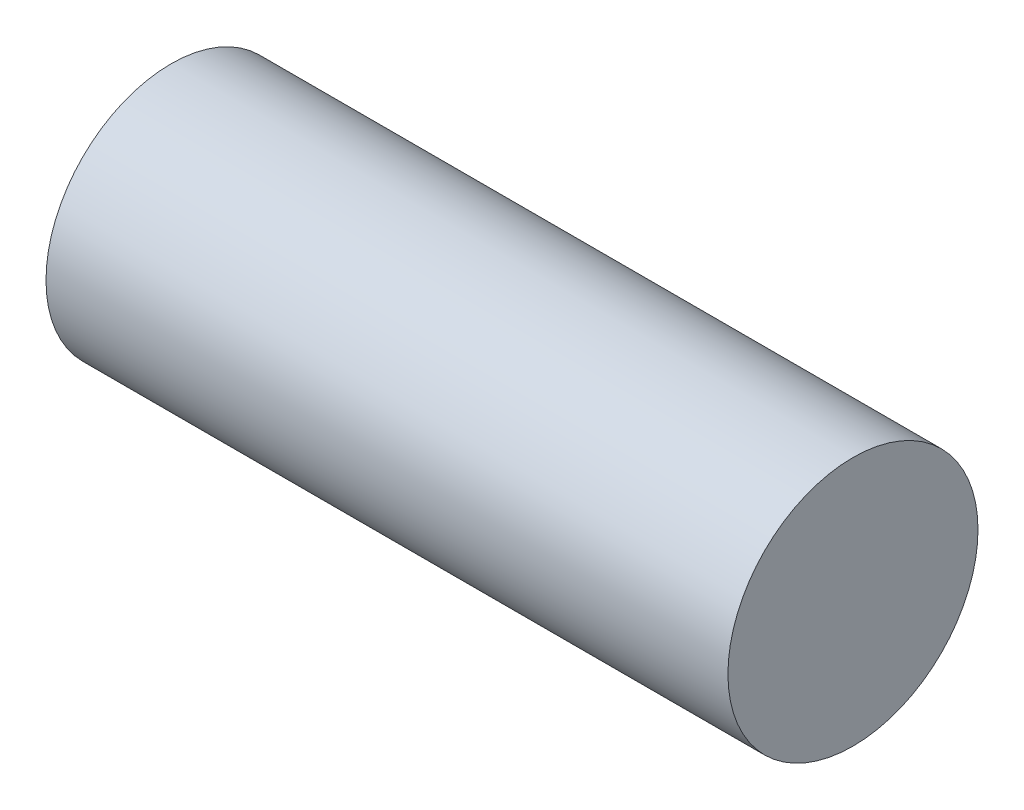
SolidWorks part; units mm, degrees
material "AISI 4340 Steel, normalized"
ref_plane "Front Plane" through (0, 0, 0) normal (0, 0, 1) x (1, 0, 0)
ref_plane "Top Plane" through (0, 0, 0) normal (0, 1, 0) x (1, 0, 0)
ref_plane "Right Plane" through (0, 0, 0) normal (1, 0, 0) x (0, 0, -1)
sketch "Sketch1" plane through (0, 0, 0) normal (1, 0, 0) x (0, 0, -1)
  circle A0 centre (0, 0) radius 38.1
  dimension "D1" = 76.2
extrude "Boss-Extrude1" add sketch "Sketch1" along normal blind 210
sketch "Sketch2" plane through (0, 0, 0) normal (-1, 0, 0) x (0, 0, 1)
  circle A1 centre (0, 0) radius 38.1
  circle A2 centre (0, 0) radius 38.1
  dimension "D1" = 0
extrude "Cut-Extrude1" cut sketch "Sketch2" against normal up to surface (2.2 mm away)
